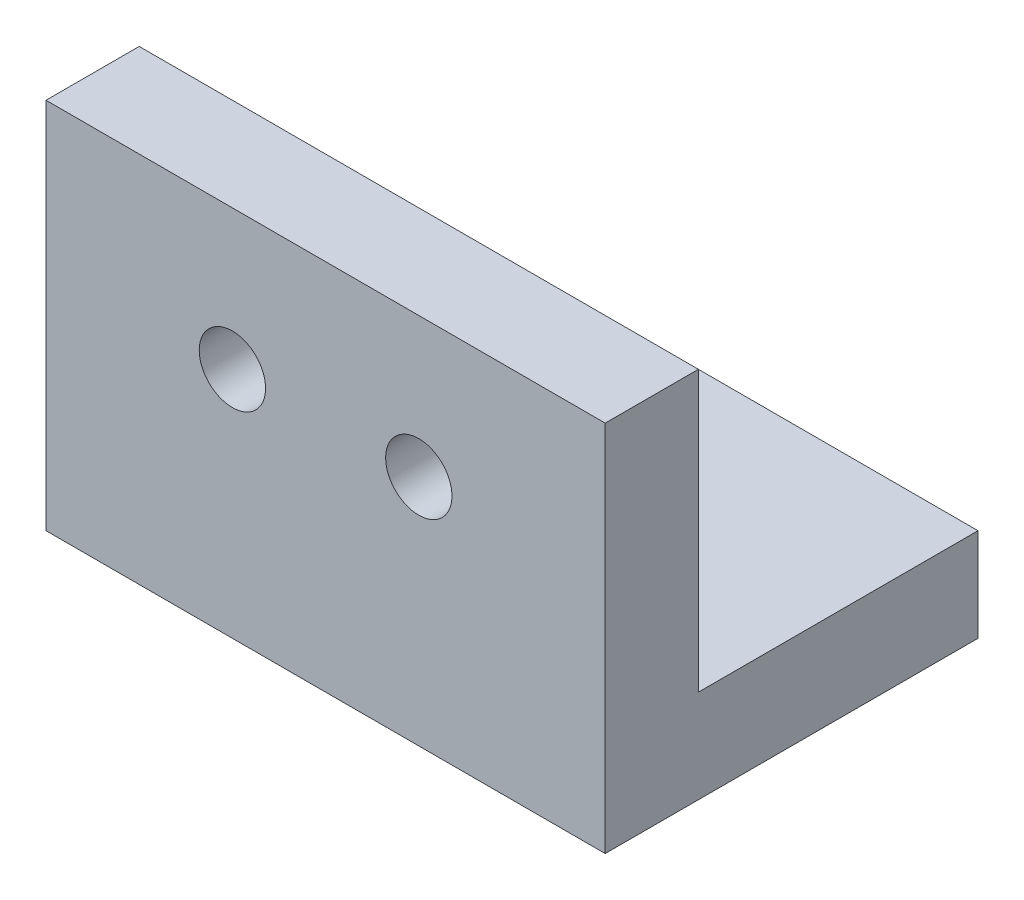
SolidWorks part; units mm, degrees
ref_plane "Front Plane" through (0, 0, 0) normal (0, 0, 1) x (1, 0, 0)
ref_plane "Top Plane" through (0, 0, 0) normal (0, 1, 0) x (1, 0, 0)
ref_plane "Right Plane" through (0, 0, 0) normal (1, 0, 0) x (0, 0, -1)
sketch "Sketch1" plane through (0, 0, 0) normal (1, 0, 0) x (0, 0, -1)
  line L0 (0, 0) -> (0, 12.7)
  line L1 (0, 12.7) -> (3.175, 12.7)
  line L2 (3.175, 12.7) -> (3.175, 3.175)
  line L3 (3.175, 3.175) -> (12.7, 3.175)
  line L4 (12.7, 3.175) -> (12.7, 0)
  line L5 (12.7, 0) -> (0, 0)
  dimension "D1" = 12.7
  dimension "D2" = 12.7
  dimension "D3" = 3.175
  dimension "D5" = 3.175
extrude "Boss-Extrude1" add sketch "Sketch1" along normal blind 19.05
hole_wizard "#43 (0.089) Diameter Hole1" positions "Sketch5" profile "Sketch4" hole size "#43" standard "ANSI Inch"
sketch "Sketch5" plane through (0, 0, -3.175) normal (0, 0, -1) x (-1, 0, 0)
  line L0 (0, 3.175) -> (0, 12.7) construction
  line L1 (-19.05, 3.175) -> (-19.05, 12.7) construction
  line L2 (-19.05, 12.7) -> (0, 12.7) construction
  point P0 (-6.35, 7.9375)
  point P2 (-12.7, 7.9375)
  dimension "D1" = 6.35
  dimension "D2" = 6.35
  dimension "D3" = 4.7625
  dimension "D4" = 4.7625
sketch "Sketch4" plane through (6.35, 7.9375, -3.175) normal (1, 0, 0) x (0, 1, 0)
  line L0 (0, 0) -> (0, 26.0792)
  line L1 (0, 26.0792) -> (1.1303, 25.4)
  line L2 (1.1303, 25.4) -> (1.1303, 0)
  line L5 (1.1303, 0) -> (0, 0)
  line L10 (0, 26.0792) -> (-1.1303, 25.4) construction
  line L11 (0, -6.35) -> (0, 107.95) construction
  dimension "Hole Dia." = 2.2606
  dimension "Hole Depth" = 25.4
  dimension "Drill Angle" = 118
hole_wizard "#43 (0.089) Diameter Hole2" positions "Sketch7" profile "Sketch6" hole size "#43" standard "ANSI Inch"
sketch "Sketch7" plane through (0, 3.175, 0) normal (0, 1, 0) x (1, 0, 0)
  line L0 (19.05, 12.7) -> (0, 12.7) construction
  line L1 (0, 12.7) -> (0, 3.175) construction
  line L2 (19.05, 12.7) -> (19.05, 3.175) construction
  point P0 (6.35, 7.9375)
  point P2 (12.7, 7.9375)
  dimension "D1" = 4.7625
  dimension "D2" = 4.7625
  dimension "D3" = 6.35
  dimension "D4" = 6.35
sketch "Sketch6" plane through (6.35, 3.175, -7.9375) normal (1, 0, 0) x (0, 0, 1)
  line L0 (0, 0) -> (0, 26.0792)
  line L1 (0, 26.0792) -> (1.1303, 25.4)
  line L2 (1.1303, 25.4) -> (1.1303, 0)
  line L5 (1.1303, 0) -> (0, 0)
  line L10 (0, 26.0792) -> (-1.1303, 25.4) construction
  line L11 (0, -6.35) -> (0, 107.95) construction
  dimension "Hole Dia." = 2.2606
  dimension "Hole Depth" = 25.4
  dimension "Drill Angle" = 118
